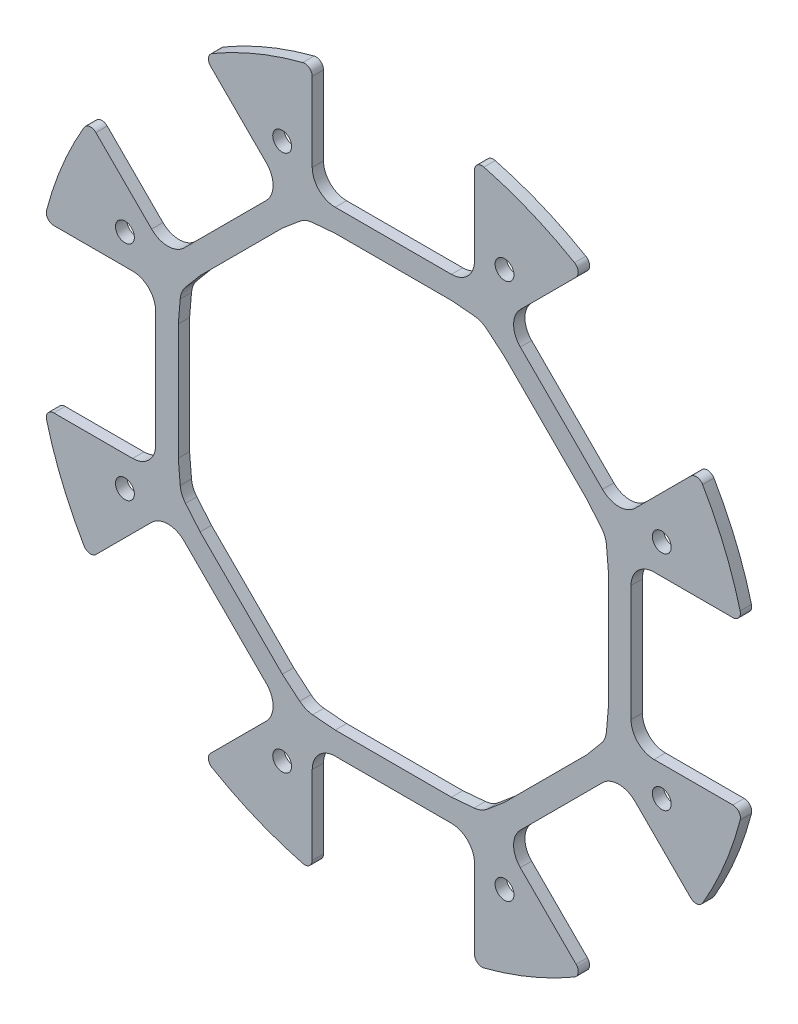
SolidWorks part; units mm, degrees
material "5052-H34"
ref_plane "正面" through (0, 0, 0) normal (0, 0, 1) x (1, 0, 0)
ref_plane "平面" through (0, 0, 0) normal (0, 1, 0) x (1, 0, 0)
ref_plane "右側面" through (0, 0, 0) normal (1, 0, 0) x (0, 0, -1)
sketch "ｽｹｯﾁ1" plane through (0, 0, 0) normal (0, 0, 1) x (1, 0, 0)
  circle A0 centre (0, 0) radius 47.5
  dimension "D1" = 95
extrude "ﾎﾞｽ - 押し出し1" add sketch "ｽｹｯﾁ1" along normal blind 1.5
sketch "ｽｹｯﾁ2" plane through (0, 0, 1.5) normal (0, 0, 1) x (1, 0, 0)
  line L0 (0, 0) -> (0, 47.5) construction
  line L1 (-10.75, 43.525) -> (-10.75, 52.5)
  line L2 (-10.75, 31.5) -> (10.75, 31.5)
  line L3 (-10.75, 31.5) -> (-10.75, 40.475)
  line L4 (-10.75, 52.5) -> (10.75, 52.5)
  line L5 (10.75, 31.5) -> (10.75, 40.475)
  line L6 (-10.75, 31.5) -> (10.75, 52.5) construction
  line L7 (-10.75, 52.5) -> (10.75, 31.5) construction
  line L8 (-13, 43.525) -> (-10.75, 43.525)
  line L9 (-13, 43.525) -> (-13, 40.475)
  line L10 (-13, 40.475) -> (-10.75, 40.475)
  line L11 (13, 43.525) -> (13, 40.475)
  line L12 (-13, 43.525) -> (13, 40.475) construction
  line L13 (-13, 40.475) -> (13, 43.525) construction
  line L14 (10.75, 43.525) -> (10.75, 52.5)
  line L15 (10.75, 43.525) -> (13, 43.525)
  line L17 (10.75, 40.475) -> (13, 40.475)
  circle A0 centre (0, 0) radius 47.5 construction
  point P5 (0, 42)
  point P10 (0, 42)
  dimension "D1" = 42
  dimension "D2" = 21.5
  dimension "D3" = 21
  dimension "D4" = 3.05
  dimension "D5" = 26
extrude "ｶｯﾄ - 押し出し1" cut sketch "ｽｹｯﾁ2" against normal through all
sketch "ｽｹｯﾁ3" plane through (0, 0, 1.5) normal (0, 0, 1) x (1, 0, 0)
  line L1 (-8.8388, -8.8388) -> (8.8388, -8.8388) construction
  line L2 (-8.8388, -8.8388) -> (-8.8388, 8.8388) construction
  line L3 (-8.8388, 8.8388) -> (8.8388, 8.8388) construction
  line L4 (8.8388, -8.8388) -> (8.8388, 8.8388) construction
  line L5 (-8.8388, -8.8388) -> (8.8388, 8.8388) construction
  line L6 (-8.8388, 8.8388) -> (8.8388, -8.8388) construction
  circle A0 centre (0, 0) radius 3.1
  circle A1 centre (0, 0) radius 6.5 construction
  circle A2 centre (0, 6.5) radius 1.6
  circle A3 centre (6.5, 0) radius 1.6
  circle A4 centre (0, -6.5) radius 1.6
  circle A5 centre (-6.5, 0) radius 1.6
  circle A6 centre (0, 0) radius 12.5 construction
  circle A7 centre (8.8388, 8.8388) radius 1.6
  circle A8 centre (8.8388, -8.8388) radius 1.6
  circle A9 centre (-8.8388, -8.8388) radius 1.6
  circle A10 centre (-8.8388, 8.8388) radius 1.6
  dimension "D1" = 6.2
  dimension "D2" = 13
  dimension "D3" = 3.2
  dimension "D5" = 25
  dimension "D6" = 3.2
  dimension "D4" = 4
  dimension "D7" = 4
extrude "ｶｯﾄ - 押し出し2" cut sketch "ｽｹｯﾁ3" against normal through all and the other way through all
sketch "ｽｹｯﾁ4" plane through (0, 0, 1.5) normal (0, 0, 1) x (1, 0, 0)
  line L0 (0, 31.5) -> (0, 0) construction
  line L1 (-10.75, 31.5) -> (10.75, 31.5) construction
  line L2 (0, 0) -> (14.7333, 35.5694) construction
  circle A0 centre (0, 0) radius 22.5 construction
  circle A1 centre (0, 0) radius 38.5 construction
  circle A2 centre (14.7333, 35.5694) radius 1.25
  circle A3 centre (8.6104, 20.7873) radius 1.25
  dimension "D1" = 45
  dimension "D2" = 77
  dimension "D4" = 2.5
  dimension "D3" = 22.5
extrude "ｶｯﾄ - 押し出し3" cut sketch "ｽｹｯﾁ4" against normal through all
sketch "ｽｹｯﾁ5" plane through (0, 0, 1.5) normal (0, 0, 1) x (1, 0, 0)
  line L0 (0, 0) -> (14.7333, 35.5694) construction
  line L1 (-10.75, 31.5) -> (10.75, 31.5) construction
  line L2 (-10.75, 31.5) -> (10.75, 31.5) construction
  line L3 (-7.1883, 26.5) -> (7.1883, 26.5)
  line L4 (-3.3281, 17.1806) -> (-7.1883, 26.5)
  line L5 (0, 31.5) -> (0, 0) construction
  line L6 (-10.75, 26.5) -> (10.75, 26.5) construction
  line L9 (-3.3281, 17.1806) -> (3.3281, 17.1806)
  line L10 (3.3281, 17.1806) -> (7.1883, 26.5)
  circle A0 centre (0, 0) radius 17.5 construction
  dimension "D3" = 35
  dimension "D2" = 7
  dimension "D1" = 5
extrude "ｶｯﾄ - 押し出し4" cut sketch "ｽｹｯﾁ5" against normal through all and the other way through all
fillet "ﾌｨﾚｯﾄ1" radius 1 6 edges at (-3.3281, 17.1806, 0.75) (3.3281, 17.1806, 0.75) (7.1883, 26.5, 0.75) (-7.1883, 26.5, 0.75) (10.75, 46.2676, 0.75) (-10.75, 46.2676, 0.75)
fillet "ﾌｨﾚｯﾄ2" radius 0.2 4 edges at (13, 43.525, 0.75) (13, 40.475, 0.75) (-13, 43.525, 0.75) (-13, 40.475, 0.75)
fillet "ﾌｨﾚｯﾄ3" radius 3.05 2 edges at (10.75, 31.5, 0.75) (-10.75, 31.5, 0.75)
ref_axis "軸1" through (0, 0, 0) along (0, 0, 1)
pattern_circular "円形ﾊﾟﾀｰﾝ1" count 8 over 360 about axis through (0, 0, 0) along (0, 0, 1) of "ｶｯﾄ - 押し出し1", "ﾌｨﾚｯﾄ1", "ｶｯﾄ - 押し出し4", "ｶｯﾄ - 押し出し3", "ﾌｨﾚｯﾄ2", "ﾌｨﾚｯﾄ3"
sketch "ｽｹｯﾁ6" plane through (0, 0, 1.5) normal (0, 0, 1) x (1, 0, 0)
  line L0 (7.7, 28.5) -> (-7.7, 28.5)
  line L1 (7.7, 28.5) -> (16.8291, 27.7186)
  line L2 (-7.7, 28.5) -> (-16.8291, 27.7186)
  line L3 (14.7078, 25.5973) -> (7.7, 31.5)
  line L4 (25.5973, 14.7078) -> (14.7078, 25.5973)
  line L5 (25.5973, 14.7078) -> (31.5, 7.7)
  line L6 (28.5, 7.7) -> (27.7186, 16.8291)
  line L7 (28.5, -7.7) -> (28.5, 7.7)
  line L8 (28.5, -7.7) -> (27.7186, -16.8291)
  line L9 (25.5973, -14.7078) -> (31.5, -7.7)
  line L10 (14.7078, -25.5973) -> (25.5973, -14.7078)
  line L11 (14.7078, -25.5973) -> (7.7, -31.5)
  line L12 (7.7, -28.5) -> (16.8291, -27.7186)
  line L13 (-7.7, -28.5) -> (7.7, -28.5)
  line L14 (-7.7, -28.5) -> (-16.8291, -27.7186)
  line L15 (-14.7078, -25.5973) -> (-7.7, -31.5)
  line L16 (-25.5973, -14.7078) -> (-14.7078, -25.5973)
  line L17 (-25.5973, -14.7078) -> (-31.5, -7.7)
  line L18 (-28.5, -7.7) -> (-27.7186, -16.8291)
  line L19 (-28.5, 7.7) -> (-28.5, -7.7)
  line L20 (-28.5, 7.7) -> (-27.7186, 16.8291)
  line L21 (-25.5973, 14.7078) -> (-31.5, 7.7)
  line L22 (-14.7078, 25.5973) -> (-25.5973, 14.7078)
  line L23 (-14.7078, 25.5973) -> (-7.7, 31.5)
  line L88 (39.4148, 24.212) -> (38.3782, 23.1754)
  line L89 (38.3782, 23.1754) -> (39.8278, 21.7259)
  line L90 (39.8278, 21.443) -> (37.954, 19.5692)
  line L91 (37.6711, 19.5692) -> (36.2215, 21.0187)
  line L92 (36.2215, 21.0187) -> (32.0319, 16.8291)
  line L93 (27.7186, 16.8291) -> (16.8291, 27.7186)
  line L94 (16.8291, 32.0319) -> (21.0187, 36.2215)
  line L95 (21.0187, 36.2215) -> (19.5692, 37.6711)
  line L96 (19.5692, 37.954) -> (21.443, 39.8278)
  line L97 (21.7259, 39.8278) -> (23.1754, 38.3782)
  line L98 (23.1754, 38.3782) -> (24.212, 39.4148)
  line L99 (10.75, 44.991) -> (10.75, 43.525)
  line L100 (10.75, 43.525) -> (12.8, 43.525)
  line L101 (13, 43.325) -> (13, 40.675)
  line L102 (12.8, 40.475) -> (10.75, 40.475)
  line L103 (10.75, 40.475) -> (10.75, 34.55)
  line L104 (7.7, 31.5) -> (-7.7, 31.5)
  line L105 (-10.75, 34.55) -> (-10.75, 40.475)
  line L106 (-10.75, 40.475) -> (-12.8, 40.475)
  line L107 (-13, 40.675) -> (-13, 43.325)
  line L108 (-12.8, 43.525) -> (-10.75, 43.525)
  line L109 (-10.75, 43.525) -> (-10.75, 44.991)
  line L110 (-24.212, 39.4148) -> (-23.1754, 38.3782)
  line L111 (-23.1754, 38.3782) -> (-21.7259, 39.8278)
  line L112 (-21.443, 39.8278) -> (-19.5692, 37.954)
  line L113 (-19.5692, 37.6711) -> (-21.0187, 36.2215)
  line L114 (-21.0187, 36.2215) -> (-16.8291, 32.0319)
  line L115 (-16.8291, 27.7186) -> (-27.7186, 16.8291)
  line L116 (-32.0319, 16.8291) -> (-36.2215, 21.0187)
  line L117 (-36.2215, 21.0187) -> (-37.6711, 19.5692)
  line L118 (-37.954, 19.5692) -> (-39.8278, 21.443)
  line L119 (-39.8278, 21.7259) -> (-38.3782, 23.1754)
  line L120 (-38.3782, 23.1754) -> (-39.4148, 24.212)
  line L121 (-44.991, 10.75) -> (-43.525, 10.75)
  line L122 (-43.525, 10.75) -> (-43.525, 12.8)
  line L123 (-43.325, 13) -> (-40.675, 13)
  line L124 (-40.475, 12.8) -> (-40.475, 10.75)
  line L125 (-40.475, 10.75) -> (-34.55, 10.75)
  line L126 (-31.5, 7.7) -> (-31.5, -7.7)
  line L127 (-34.55, -10.75) -> (-40.475, -10.75)
  line L128 (-40.475, -10.75) -> (-40.475, -12.8)
  line L129 (-40.675, -13) -> (-43.325, -13)
  line L130 (-43.525, -12.8) -> (-43.525, -10.75)
  line L131 (-43.525, -10.75) -> (-44.991, -10.75)
  line L132 (-39.4148, -24.212) -> (-38.3782, -23.1754)
  line L133 (-38.3782, -23.1754) -> (-39.8278, -21.7259)
  line L134 (-39.8278, -21.443) -> (-37.954, -19.5692)
  line L135 (-37.6711, -19.5692) -> (-36.2215, -21.0187)
  line L136 (-36.2215, -21.0187) -> (-32.0319, -16.8291)
  line L137 (-27.7186, -16.8291) -> (-16.8291, -27.7186)
  line L138 (-16.8291, -32.0319) -> (-21.0187, -36.2215)
  line L139 (-21.0187, -36.2215) -> (-19.5692, -37.6711)
  line L140 (-19.5692, -37.954) -> (-21.443, -39.8278)
  line L141 (-21.7259, -39.8278) -> (-23.1754, -38.3782)
  line L142 (-23.1754, -38.3782) -> (-24.212, -39.4148)
  line L143 (-10.75, -44.991) -> (-10.75, -43.525)
  line L144 (-10.75, -43.525) -> (-12.8, -43.525)
  line L145 (-13, -43.325) -> (-13, -40.675)
  line L146 (-12.8, -40.475) -> (-10.75, -40.475)
  line L147 (-10.75, -40.475) -> (-10.75, -34.55)
  line L148 (-7.7, -31.5) -> (7.7, -31.5)
  line L149 (10.75, -34.55) -> (10.75, -40.475)
  line L150 (10.75, -40.475) -> (12.8, -40.475)
  line L151 (13, -40.675) -> (13, -43.325)
  line L152 (12.8, -43.525) -> (10.75, -43.525)
  line L153 (10.75, -43.525) -> (10.75, -44.991)
  line L154 (24.212, -39.4148) -> (23.1754, -38.3782)
  line L155 (23.1754, -38.3782) -> (21.7259, -39.8278)
  line L156 (21.443, -39.8278) -> (19.5692, -37.954)
  line L157 (19.5692, -37.6711) -> (21.0187, -36.2215)
  line L158 (21.0187, -36.2215) -> (16.8291, -32.0319)
  line L159 (16.8291, -27.7186) -> (27.7186, -16.8291)
  line L160 (32.0319, -16.8291) -> (36.2215, -21.0187)
  line L161 (36.2215, -21.0187) -> (37.6711, -19.5692)
  line L162 (37.954, -19.5692) -> (39.8278, -21.443)
  line L163 (39.8278, -21.7259) -> (38.3782, -23.1754)
  line L164 (38.3782, -23.1754) -> (39.4148, -24.212)
  line L165 (44.991, -10.75) -> (43.525, -10.75)
  line L166 (43.525, -10.75) -> (43.525, -12.8)
  line L167 (43.325, -13) -> (40.675, -13)
  line L168 (40.475, -12.8) -> (40.475, -10.75)
  line L169 (40.475, -10.75) -> (34.55, -10.75)
  line L170 (31.5, -7.7) -> (31.5, 7.7)
  line L171 (34.55, 10.75) -> (40.475, 10.75)
  line L172 (40.475, 10.75) -> (40.475, 12.8)
  line L173 (40.675, 13) -> (43.325, 13)
  line L174 (43.525, 12.8) -> (43.525, 10.75)
  line L175 (43.525, 10.75) -> (44.991, 10.75)
  line L176 (39.4148, 24.212) -> (38.3782, 23.1754)
  line L177 (38.3782, 23.1754) -> (39.8278, 21.7259)
  line L178 (39.8278, 21.443) -> (37.954, 19.5692)
  line L179 (37.6711, 19.5692) -> (36.2215, 21.0187)
  line L180 (36.2215, 21.0187) -> (32.0319, 16.8291)
  line L181 (27.7186, 16.8291) -> (16.8291, 27.7186)
  line L182 (16.8291, 32.0319) -> (21.0187, 36.2215)
  line L183 (21.0187, 36.2215) -> (19.5692, 37.6711)
  line L184 (19.5692, 37.954) -> (21.443, 39.8278)
  line L185 (21.7259, 39.8278) -> (23.1754, 38.3782)
  line L186 (23.1754, 38.3782) -> (24.212, 39.4148)
  line L187 (10.75, 44.991) -> (10.75, 43.525)
  line L188 (10.75, 43.525) -> (12.8, 43.525)
  line L189 (13, 43.325) -> (13, 40.675)
  line L190 (12.8, 40.475) -> (10.75, 40.475)
  line L191 (10.75, 40.475) -> (10.75, 34.55)
  line L192 (7.7, 31.5) -> (-7.7, 31.5)
  line L193 (-10.75, 34.55) -> (-10.75, 40.475)
  line L194 (-10.75, 40.475) -> (-12.8, 40.475)
  line L195 (-13, 40.675) -> (-13, 43.325)
  line L196 (-12.8, 43.525) -> (-10.75, 43.525)
  line L197 (-10.75, 43.525) -> (-10.75, 44.991)
  line L198 (-24.212, 39.4148) -> (-23.1754, 38.3782)
  line L199 (-23.1754, 38.3782) -> (-21.7259, 39.8278)
  line L200 (-21.443, 39.8278) -> (-19.5692, 37.954)
  line L201 (-19.5692, 37.6711) -> (-21.0187, 36.2215)
  line L202 (-21.0187, 36.2215) -> (-16.8291, 32.0319)
  line L203 (-16.8291, 27.7186) -> (-27.7186, 16.8291)
  line L204 (-32.0319, 16.8291) -> (-36.2215, 21.0187)
  line L205 (-36.2215, 21.0187) -> (-37.6711, 19.5692)
  line L206 (-37.954, 19.5692) -> (-39.8278, 21.443)
  line L207 (-39.8278, 21.7259) -> (-38.3782, 23.1754)
  line L208 (-38.3782, 23.1754) -> (-39.4148, 24.212)
  line L209 (-44.991, 10.75) -> (-43.525, 10.75)
  line L210 (-43.525, 10.75) -> (-43.525, 12.8)
  line L211 (-43.325, 13) -> (-40.675, 13)
  line L212 (-40.475, 12.8) -> (-40.475, 10.75)
  line L213 (-40.475, 10.75) -> (-34.55, 10.75)
  line L214 (-31.5, 7.7) -> (-31.5, -7.7)
  line L215 (-34.55, -10.75) -> (-40.475, -10.75)
  line L216 (-40.475, -10.75) -> (-40.475, -12.8)
  line L217 (-40.675, -13) -> (-43.325, -13)
  line L218 (-43.525, -12.8) -> (-43.525, -10.75)
  line L219 (-43.525, -10.75) -> (-44.991, -10.75)
  line L220 (-39.4148, -24.212) -> (-38.3782, -23.1754)
  line L221 (-38.3782, -23.1754) -> (-39.8278, -21.7259)
  line L222 (-39.8278, -21.443) -> (-37.954, -19.5692)
  line L223 (-37.6711, -19.5692) -> (-36.2215, -21.0187)
  line L224 (-36.2215, -21.0187) -> (-32.0319, -16.8291)
  line L225 (-27.7186, -16.8291) -> (-16.8291, -27.7186)
  line L226 (-16.8291, -32.0319) -> (-21.0187, -36.2215)
  line L227 (-21.0187, -36.2215) -> (-19.5692, -37.6711)
  line L228 (-19.5692, -37.954) -> (-21.443, -39.8278)
  line L229 (-21.7259, -39.8278) -> (-23.1754, -38.3782)
  line L230 (-23.1754, -38.3782) -> (-24.212, -39.4148)
  line L231 (-10.75, -44.991) -> (-10.75, -43.525)
  line L232 (-10.75, -43.525) -> (-12.8, -43.525)
  line L233 (-13, -43.325) -> (-13, -40.675)
  line L234 (-12.8, -40.475) -> (-10.75, -40.475)
  line L235 (-10.75, -40.475) -> (-10.75, -34.55)
  line L236 (-7.7, -31.5) -> (7.7, -31.5)
  line L237 (10.75, -34.55) -> (10.75, -40.475)
  line L238 (10.75, -40.475) -> (12.8, -40.475)
  line L239 (13, -40.675) -> (13, -43.325)
  line L240 (12.8, -43.525) -> (10.75, -43.525)
  line L241 (10.75, -43.525) -> (10.75, -44.991)
  line L242 (24.212, -39.4148) -> (23.1754, -38.3782)
  line L243 (23.1754, -38.3782) -> (21.7259, -39.8278)
  line L244 (21.443, -39.8278) -> (19.5692, -37.954)
  line L245 (19.5692, -37.6711) -> (21.0187, -36.2215)
  line L246 (21.0187, -36.2215) -> (16.8291, -32.0319)
  line L247 (16.8291, -27.7186) -> (27.7186, -16.8291)
  line L248 (32.0319, -16.8291) -> (36.2215, -21.0187)
  line L249 (36.2215, -21.0187) -> (37.6711, -19.5692)
  line L250 (37.954, -19.5692) -> (39.8278, -21.443)
  line L251 (39.8278, -21.7259) -> (38.3782, -23.1754)
  line L252 (38.3782, -23.1754) -> (39.4148, -24.212)
  line L253 (44.991, -10.75) -> (43.525, -10.75)
  line L254 (43.525, -10.75) -> (43.525, -12.8)
  line L255 (43.325, -13) -> (40.675, -13)
  line L256 (40.475, -12.8) -> (40.475, -10.75)
  line L257 (40.475, -10.75) -> (34.55, -10.75)
  line L258 (31.5, -7.7) -> (31.5, 7.7)
  line L259 (34.55, 10.75) -> (40.475, 10.75)
  line L260 (40.475, 10.75) -> (40.475, 12.8)
  line L261 (40.675, 13) -> (43.325, 13)
  line L262 (43.525, 12.8) -> (43.525, 10.75)
  line L263 (43.525, 10.75) -> (44.991, 10.75)
  arc A72 (45.9585, 12.0027) -> (40.9848, 24.0104) centre (0, 0) ccw
  arc A73 (40.9848, 24.0104) -> (39.4148, 24.212) centre (40.1219, 23.5049) ccw
  arc A74 (39.8278, 21.443) -> (39.8278, 21.7259) centre (39.6864, 21.5844) ccw
  arc A75 (37.6711, 19.5692) -> (37.954, 19.5692) centre (37.8125, 19.7106) ccw
  arc A76 (27.7186, 16.8291) -> (32.0319, 16.8291) centre (29.8753, 18.9858) ccw
  arc A77 (16.8291, 32.0319) -> (16.8291, 27.7186) centre (18.9858, 29.8753) ccw
  arc A78 (19.5692, 37.954) -> (19.5692, 37.6711) centre (19.7106, 37.8125) ccw
  arc A79 (21.7259, 39.8278) -> (21.443, 39.8278) centre (21.5844, 39.6864) ccw
  arc A80 (24.212, 39.4148) -> (24.0104, 40.9848) centre (23.5049, 40.1219) ccw
  arc A81 (24.0104, 40.9848) -> (12.0027, 45.9585) centre (0, 0) ccw
  arc A82 (12.0027, 45.9585) -> (10.75, 44.991) centre (11.75, 44.991) ccw
  arc A83 (13, 43.325) -> (12.8, 43.525) centre (12.8, 43.325) ccw
  arc A84 (12.8, 40.475) -> (13, 40.675) centre (12.8, 40.675) ccw
  arc A85 (7.7, 31.5) -> (10.75, 34.55) centre (7.7, 34.55) ccw
  arc A86 (-10.75, 34.55) -> (-7.7, 31.5) centre (-7.7, 34.55) ccw
  arc A87 (-13, 40.675) -> (-12.8, 40.475) centre (-12.8, 40.675) ccw
  arc A88 (-12.8, 43.525) -> (-13, 43.325) centre (-12.8, 43.325) ccw
  arc A89 (-10.75, 44.991) -> (-12.0027, 45.9585) centre (-11.75, 44.991) ccw
  arc A90 (-12.0027, 45.9585) -> (-24.0104, 40.9848) centre (0, 0) ccw
  arc A91 (-24.0104, 40.9848) -> (-24.212, 39.4148) centre (-23.5049, 40.1219) ccw
  arc A92 (-21.443, 39.8278) -> (-21.7259, 39.8278) centre (-21.5844, 39.6864) ccw
  arc A93 (-19.5692, 37.6711) -> (-19.5692, 37.954) centre (-19.7106, 37.8125) ccw
  arc A94 (-16.8291, 27.7186) -> (-16.8291, 32.0319) centre (-18.9858, 29.8753) ccw
  arc A95 (-32.0319, 16.8291) -> (-27.7186, 16.8291) centre (-29.8753, 18.9858) ccw
  arc A96 (-37.954, 19.5692) -> (-37.6711, 19.5692) centre (-37.8125, 19.7106) ccw
  arc A97 (-39.8278, 21.7259) -> (-39.8278, 21.443) centre (-39.6864, 21.5844) ccw
  arc A98 (-39.4148, 24.212) -> (-40.9848, 24.0104) centre (-40.1219, 23.5049) ccw
  arc A99 (-40.9848, 24.0104) -> (-45.9585, 12.0027) centre (0, 0) ccw
  arc A100 (-45.9585, 12.0027) -> (-44.991, 10.75) centre (-44.991, 11.75) ccw
  arc A101 (-43.325, 13) -> (-43.525, 12.8) centre (-43.325, 12.8) ccw
  arc A102 (-40.475, 12.8) -> (-40.675, 13) centre (-40.675, 12.8) ccw
  arc A103 (-31.5, 7.7) -> (-34.55, 10.75) centre (-34.55, 7.7) ccw
  arc A104 (-34.55, -10.75) -> (-31.5, -7.7) centre (-34.55, -7.7) ccw
  arc A105 (-40.675, -13) -> (-40.475, -12.8) centre (-40.675, -12.8) ccw
  arc A106 (-43.525, -12.8) -> (-43.325, -13) centre (-43.325, -12.8) ccw
  arc A107 (-44.991, -10.75) -> (-45.9585, -12.0027) centre (-44.991, -11.75) ccw
  arc A108 (-45.9585, -12.0027) -> (-40.9848, -24.0104) centre (0, 0) ccw
  arc A109 (-40.9848, -24.0104) -> (-39.4148, -24.212) centre (-40.1219, -23.5049) ccw
  arc A110 (-39.8278, -21.443) -> (-39.8278, -21.7259) centre (-39.6864, -21.5844) ccw
  arc A111 (-37.6711, -19.5692) -> (-37.954, -19.5692) centre (-37.8125, -19.7106) ccw
  arc A112 (-27.7186, -16.8291) -> (-32.0319, -16.8291) centre (-29.8753, -18.9858) ccw
  arc A113 (-16.8291, -32.0319) -> (-16.8291, -27.7186) centre (-18.9858, -29.8753) ccw
  arc A114 (-19.5692, -37.954) -> (-19.5692, -37.6711) centre (-19.7106, -37.8125) ccw
  arc A115 (-21.7259, -39.8278) -> (-21.443, -39.8278) centre (-21.5844, -39.6864) ccw
  arc A116 (-24.212, -39.4148) -> (-24.0104, -40.9848) centre (-23.5049, -40.1219) ccw
  arc A117 (-24.0104, -40.9848) -> (-12.0027, -45.9585) centre (0, 0) ccw
  arc A118 (-12.0027, -45.9585) -> (-10.75, -44.991) centre (-11.75, -44.991) ccw
  arc A119 (-13, -43.325) -> (-12.8, -43.525) centre (-12.8, -43.325) ccw
  arc A120 (-12.8, -40.475) -> (-13, -40.675) centre (-12.8, -40.675) ccw
  arc A121 (-7.7, -31.5) -> (-10.75, -34.55) centre (-7.7, -34.55) ccw
  arc A122 (10.75, -34.55) -> (7.7, -31.5) centre (7.7, -34.55) ccw
  arc A123 (13, -40.675) -> (12.8, -40.475) centre (12.8, -40.675) ccw
  arc A124 (12.8, -43.525) -> (13, -43.325) centre (12.8, -43.325) ccw
  arc A125 (10.75, -44.991) -> (12.0027, -45.9585) centre (11.75, -44.991) ccw
  arc A126 (12.0027, -45.9585) -> (24.0104, -40.9848) centre (0, 0) ccw
  arc A127 (24.0104, -40.9848) -> (24.212, -39.4148) centre (23.5049, -40.1219) ccw
  arc A128 (21.443, -39.8278) -> (21.7259, -39.8278) centre (21.5844, -39.6864) ccw
  arc A129 (19.5692, -37.6711) -> (19.5692, -37.954) centre (19.7106, -37.8125) ccw
  arc A130 (16.8291, -27.7186) -> (16.8291, -32.0319) centre (18.9858, -29.8753) ccw
  arc A131 (32.0319, -16.8291) -> (27.7186, -16.8291) centre (29.8753, -18.9858) ccw
  arc A132 (37.954, -19.5692) -> (37.6711, -19.5692) centre (37.8125, -19.7106) ccw
  arc A133 (39.8278, -21.7259) -> (39.8278, -21.443) centre (39.6864, -21.5844) ccw
  arc A134 (39.4148, -24.212) -> (40.9848, -24.0104) centre (40.1219, -23.5049) ccw
  arc A135 (40.9848, -24.0104) -> (45.9585, -12.0027) centre (0, 0) ccw
  arc A136 (45.9585, -12.0027) -> (44.991, -10.75) centre (44.991, -11.75) ccw
  arc A137 (43.325, -13) -> (43.525, -12.8) centre (43.325, -12.8) ccw
  arc A138 (40.475, -12.8) -> (40.675, -13) centre (40.675, -12.8) ccw
  arc A139 (31.5, -7.7) -> (34.55, -10.75) centre (34.55, -7.7) ccw
  arc A140 (34.55, 10.75) -> (31.5, 7.7) centre (34.55, 7.7) ccw
  arc A141 (40.675, 13) -> (40.475, 12.8) centre (40.675, 12.8) ccw
  arc A142 (43.525, 12.8) -> (43.325, 13) centre (43.325, 12.8) ccw
  arc A143 (44.991, 10.75) -> (45.9585, 12.0027) centre (44.991, 11.75) ccw
  arc A144 (45.9585, 12.0027) -> (40.9848, 24.0104) centre (0, 0) ccw
  arc A145 (40.9848, 24.0104) -> (39.4148, 24.212) centre (40.1219, 23.5049) ccw
  arc A146 (39.8278, 21.443) -> (39.8278, 21.7259) centre (39.6864, 21.5844) ccw
  arc A147 (37.6711, 19.5692) -> (37.954, 19.5692) centre (37.8125, 19.7106) ccw
  arc A148 (27.7186, 16.8291) -> (32.0319, 16.8291) centre (29.8753, 18.9858) ccw
  arc A149 (16.8291, 32.0319) -> (16.8291, 27.7186) centre (18.9858, 29.8753) ccw
  arc A150 (19.5692, 37.954) -> (19.5692, 37.6711) centre (19.7106, 37.8125) ccw
  arc A151 (21.7259, 39.8278) -> (21.443, 39.8278) centre (21.5844, 39.6864) ccw
  arc A152 (24.212, 39.4148) -> (24.0104, 40.9848) centre (23.5049, 40.1219) ccw
  arc A153 (24.0104, 40.9848) -> (12.0027, 45.9585) centre (0, 0) ccw
  arc A154 (12.0027, 45.9585) -> (10.75, 44.991) centre (11.75, 44.991) ccw
  arc A155 (13, 43.325) -> (12.8, 43.525) centre (12.8, 43.325) ccw
  arc A156 (12.8, 40.475) -> (13, 40.675) centre (12.8, 40.675) ccw
  arc A157 (7.7, 31.5) -> (10.75, 34.55) centre (7.7, 34.55) ccw
  arc A158 (-10.75, 34.55) -> (-7.7, 31.5) centre (-7.7, 34.55) ccw
  arc A159 (-13, 40.675) -> (-12.8, 40.475) centre (-12.8, 40.675) ccw
  arc A160 (-12.8, 43.525) -> (-13, 43.325) centre (-12.8, 43.325) ccw
  arc A161 (-10.75, 44.991) -> (-12.0027, 45.9585) centre (-11.75, 44.991) ccw
  arc A162 (-12.0027, 45.9585) -> (-24.0104, 40.9848) centre (0, 0) ccw
  arc A163 (-24.0104, 40.9848) -> (-24.212, 39.4148) centre (-23.5049, 40.1219) ccw
  arc A164 (-21.443, 39.8278) -> (-21.7259, 39.8278) centre (-21.5844, 39.6864) ccw
  arc A165 (-19.5692, 37.6711) -> (-19.5692, 37.954) centre (-19.7106, 37.8125) ccw
  arc A166 (-16.8291, 27.7186) -> (-16.8291, 32.0319) centre (-18.9858, 29.8753) ccw
  arc A167 (-32.0319, 16.8291) -> (-27.7186, 16.8291) centre (-29.8753, 18.9858) ccw
  arc A168 (-37.954, 19.5692) -> (-37.6711, 19.5692) centre (-37.8125, 19.7106) ccw
  arc A169 (-39.8278, 21.7259) -> (-39.8278, 21.443) centre (-39.6864, 21.5844) ccw
  arc A170 (-39.4148, 24.212) -> (-40.9848, 24.0104) centre (-40.1219, 23.5049) ccw
  arc A171 (-40.9848, 24.0104) -> (-45.9585, 12.0027) centre (0, 0) ccw
  arc A172 (-45.9585, 12.0027) -> (-44.991, 10.75) centre (-44.991, 11.75) ccw
  arc A173 (-43.325, 13) -> (-43.525, 12.8) centre (-43.325, 12.8) ccw
  arc A174 (-40.475, 12.8) -> (-40.675, 13) centre (-40.675, 12.8) ccw
  arc A175 (-31.5, 7.7) -> (-34.55, 10.75) centre (-34.55, 7.7) ccw
  arc A176 (-34.55, -10.75) -> (-31.5, -7.7) centre (-34.55, -7.7) ccw
  arc A177 (-40.675, -13) -> (-40.475, -12.8) centre (-40.675, -12.8) ccw
  arc A178 (-43.525, -12.8) -> (-43.325, -13) centre (-43.325, -12.8) ccw
  arc A179 (-44.991, -10.75) -> (-45.9585, -12.0027) centre (-44.991, -11.75) ccw
  arc A180 (-45.9585, -12.0027) -> (-40.9848, -24.0104) centre (0, 0) ccw
  arc A181 (-40.9848, -24.0104) -> (-39.4148, -24.212) centre (-40.1219, -23.5049) ccw
  arc A182 (-39.8278, -21.443) -> (-39.8278, -21.7259) centre (-39.6864, -21.5844) ccw
  arc A183 (-37.6711, -19.5692) -> (-37.954, -19.5692) centre (-37.8125, -19.7106) ccw
  arc A184 (-27.7186, -16.8291) -> (-32.0319, -16.8291) centre (-29.8753, -18.9858) ccw
  arc A185 (-16.8291, -32.0319) -> (-16.8291, -27.7186) centre (-18.9858, -29.8753) ccw
  arc A186 (-19.5692, -37.954) -> (-19.5692, -37.6711) centre (-19.7106, -37.8125) ccw
  arc A187 (-21.7259, -39.8278) -> (-21.443, -39.8278) centre (-21.5844, -39.6864) ccw
  arc A188 (-24.212, -39.4148) -> (-24.0104, -40.9848) centre (-23.5049, -40.1219) ccw
  arc A189 (-24.0104, -40.9848) -> (-12.0027, -45.9585) centre (0, 0) ccw
  arc A190 (-12.0027, -45.9585) -> (-10.75, -44.991) centre (-11.75, -44.991) ccw
  arc A191 (-13, -43.325) -> (-12.8, -43.525) centre (-12.8, -43.325) ccw
  arc A192 (-12.8, -40.475) -> (-13, -40.675) centre (-12.8, -40.675) ccw
  arc A193 (-7.7, -31.5) -> (-10.75, -34.55) centre (-7.7, -34.55) ccw
  arc A194 (10.75, -34.55) -> (7.7, -31.5) centre (7.7, -34.55) ccw
  arc A195 (13, -40.675) -> (12.8, -40.475) centre (12.8, -40.675) ccw
  arc A196 (12.8, -43.525) -> (13, -43.325) centre (12.8, -43.325) ccw
  arc A197 (10.75, -44.991) -> (12.0027, -45.9585) centre (11.75, -44.991) ccw
  arc A198 (12.0027, -45.9585) -> (24.0104, -40.9848) centre (0, 0) ccw
  arc A199 (24.0104, -40.9848) -> (24.212, -39.4148) centre (23.5049, -40.1219) ccw
  arc A200 (21.443, -39.8278) -> (21.7259, -39.8278) centre (21.5844, -39.6864) ccw
  arc A201 (19.5692, -37.6711) -> (19.5692, -37.954) centre (19.7106, -37.8125) ccw
  arc A202 (16.8291, -27.7186) -> (16.8291, -32.0319) centre (18.9858, -29.8753) ccw
  arc A203 (32.0319, -16.8291) -> (27.7186, -16.8291) centre (29.8753, -18.9858) ccw
  arc A204 (37.954, -19.5692) -> (37.6711, -19.5692) centre (37.8125, -19.7106) ccw
  arc A205 (39.8278, -21.7259) -> (39.8278, -21.443) centre (39.6864, -21.5844) ccw
  arc A206 (39.4148, -24.212) -> (40.9848, -24.0104) centre (40.1219, -23.5049) ccw
  arc A207 (40.9848, -24.0104) -> (45.9585, -12.0027) centre (0, 0) ccw
  arc A208 (45.9585, -12.0027) -> (44.991, -10.75) centre (44.991, -11.75) ccw
  arc A209 (43.325, -13) -> (43.525, -12.8) centre (43.325, -12.8) ccw
  arc A210 (40.475, -12.8) -> (40.675, -13) centre (40.675, -12.8) ccw
  arc A211 (31.5, -7.7) -> (34.55, -10.75) centre (34.55, -7.7) ccw
  arc A212 (34.55, 10.75) -> (31.5, 7.7) centre (34.55, 7.7) ccw
  arc A213 (40.675, 13) -> (40.475, 12.8) centre (40.675, 12.8) ccw
  arc A214 (43.525, 12.8) -> (43.325, 13) centre (43.325, 12.8) ccw
  arc A215 (44.991, 10.75) -> (45.9585, 12.0027) centre (44.991, 11.75) ccw
  dimension "D4" = 3
  dimension "D5" = 3
  dimension "D1" = 0
  dimension "D2" = 3
  dimension "D3" = 8
extrude "ｶｯﾄ - 押し出し5" cut sketch "ｽｹｯﾁ6" against normal through all contours L23 L22 L21 L20 L19 L18 L17 L16 L15 L14 L13 L12 L11 L10 L9 L8 L7 L6 L5 L4 L3 L1 L0 L2
sketch "ｽｹｯﾁ7" plane through (0, 0, 1.5) normal (0, 0, 1) x (1, 0, 0)
  line L0 (-10.75, 43.525) -> (-10.75, 40.475)
  line L1 (10.75, 43.525) -> (10.75, 40.475)
  line L2 (23.1754, 38.3782) -> (21.0187, 36.2215)
  line L3 (38.3782, 23.1754) -> (36.2215, 21.0187)
  line L4 (43.525, 10.75) -> (40.475, 10.75)
  line L5 (43.525, -10.75) -> (40.475, -10.75)
  line L6 (38.3782, -23.1754) -> (36.2215, -21.0187)
  line L7 (23.1754, -38.3782) -> (21.0187, -36.2215)
  line L8 (10.75, -43.525) -> (10.75, -40.475)
  line L9 (-10.75, -43.525) -> (-10.75, -40.475)
  line L10 (-23.1754, -38.3782) -> (-21.0187, -36.2215)
  line L11 (-38.3782, -23.1754) -> (-36.2215, -21.0187)
  line L12 (-43.525, -10.75) -> (-40.475, -10.75)
  line L13 (-43.525, 10.75) -> (-40.475, 10.75)
  line L14 (-38.3782, 23.1754) -> (-36.2215, 21.0187)
  line L15 (-23.1754, 38.3782) -> (-21.0187, 36.2215)
  line L88 (39.4148, 24.212) -> (38.3782, 23.1754)
  line L89 (38.3782, 23.1754) -> (39.8278, 21.7259)
  line L90 (39.8278, 21.443) -> (37.954, 19.5692)
  line L91 (37.6711, 19.5692) -> (36.2215, 21.0187)
  line L92 (36.2215, 21.0187) -> (32.0319, 16.8291)
  line L93 (27.7186, 16.8291) -> (16.8291, 27.7186)
  line L94 (16.8291, 32.0319) -> (21.0187, 36.2215)
  line L95 (21.0187, 36.2215) -> (19.5692, 37.6711)
  line L96 (19.5692, 37.954) -> (21.443, 39.8278)
  line L97 (21.7259, 39.8278) -> (23.1754, 38.3782)
  line L98 (23.1754, 38.3782) -> (24.212, 39.4148)
  line L99 (10.75, 44.991) -> (10.75, 43.525)
  line L100 (10.75, 43.525) -> (12.8, 43.525)
  line L101 (13, 43.325) -> (13, 40.675)
  line L102 (12.8, 40.475) -> (10.75, 40.475)
  line L103 (10.75, 40.475) -> (10.75, 34.55)
  line L104 (7.7, 31.5) -> (-7.7, 31.5)
  line L105 (-10.75, 34.55) -> (-10.75, 40.475)
  line L106 (-10.75, 40.475) -> (-12.8, 40.475)
  line L107 (-13, 40.675) -> (-13, 43.325)
  line L108 (-12.8, 43.525) -> (-10.75, 43.525)
  line L109 (-10.75, 43.525) -> (-10.75, 44.991)
  line L110 (-24.212, 39.4148) -> (-23.1754, 38.3782)
  line L111 (-23.1754, 38.3782) -> (-21.7259, 39.8278)
  line L112 (-21.443, 39.8278) -> (-19.5692, 37.954)
  line L113 (-19.5692, 37.6711) -> (-21.0187, 36.2215)
  line L114 (-21.0187, 36.2215) -> (-16.8291, 32.0319)
  line L115 (-16.8291, 27.7186) -> (-27.7186, 16.8291)
  line L116 (-32.0319, 16.8291) -> (-36.2215, 21.0187)
  line L117 (-36.2215, 21.0187) -> (-37.6711, 19.5692)
  line L118 (-37.954, 19.5692) -> (-39.8278, 21.443)
  line L119 (-39.8278, 21.7259) -> (-38.3782, 23.1754)
  line L120 (-38.3782, 23.1754) -> (-39.4148, 24.212)
  line L121 (-44.991, 10.75) -> (-43.525, 10.75)
  line L122 (-43.525, 10.75) -> (-43.525, 12.8)
  line L123 (-43.325, 13) -> (-40.675, 13)
  line L124 (-40.475, 12.8) -> (-40.475, 10.75)
  line L125 (-40.475, 10.75) -> (-34.55, 10.75)
  line L126 (-31.5, 7.7) -> (-31.5, -7.7)
  line L127 (-34.55, -10.75) -> (-40.475, -10.75)
  line L128 (-40.475, -10.75) -> (-40.475, -12.8)
  line L129 (-40.675, -13) -> (-43.325, -13)
  line L130 (-43.525, -12.8) -> (-43.525, -10.75)
  line L131 (-43.525, -10.75) -> (-44.991, -10.75)
  line L132 (-39.4148, -24.212) -> (-38.3782, -23.1754)
  line L133 (-38.3782, -23.1754) -> (-39.8278, -21.7259)
  line L134 (-39.8278, -21.443) -> (-37.954, -19.5692)
  line L135 (-37.6711, -19.5692) -> (-36.2215, -21.0187)
  line L136 (-36.2215, -21.0187) -> (-32.0319, -16.8291)
  line L137 (-27.7186, -16.8291) -> (-16.8291, -27.7186)
  line L138 (-16.8291, -32.0319) -> (-21.0187, -36.2215)
  line L139 (-21.0187, -36.2215) -> (-19.5692, -37.6711)
  line L140 (-19.5692, -37.954) -> (-21.443, -39.8278)
  line L141 (-21.7259, -39.8278) -> (-23.1754, -38.3782)
  line L142 (-23.1754, -38.3782) -> (-24.212, -39.4148)
  line L143 (-10.75, -44.991) -> (-10.75, -43.525)
  line L144 (-10.75, -43.525) -> (-12.8, -43.525)
  line L145 (-13, -43.325) -> (-13, -40.675)
  line L146 (-12.8, -40.475) -> (-10.75, -40.475)
  line L147 (-10.75, -40.475) -> (-10.75, -34.55)
  line L148 (-7.7, -31.5) -> (7.7, -31.5)
  line L149 (10.75, -34.55) -> (10.75, -40.475)
  line L150 (10.75, -40.475) -> (12.8, -40.475)
  line L151 (13, -40.675) -> (13, -43.325)
  line L152 (12.8, -43.525) -> (10.75, -43.525)
  line L153 (10.75, -43.525) -> (10.75, -44.991)
  line L154 (24.212, -39.4148) -> (23.1754, -38.3782)
  line L155 (23.1754, -38.3782) -> (21.7259, -39.8278)
  line L156 (21.443, -39.8278) -> (19.5692, -37.954)
  line L157 (19.5692, -37.6711) -> (21.0187, -36.2215)
  line L158 (21.0187, -36.2215) -> (16.8291, -32.0319)
  line L159 (16.8291, -27.7186) -> (27.7186, -16.8291)
  line L160 (32.0319, -16.8291) -> (36.2215, -21.0187)
  line L161 (36.2215, -21.0187) -> (37.6711, -19.5692)
  line L162 (37.954, -19.5692) -> (39.8278, -21.443)
  line L163 (39.8278, -21.7259) -> (38.3782, -23.1754)
  line L164 (38.3782, -23.1754) -> (39.4148, -24.212)
  line L165 (44.991, -10.75) -> (43.525, -10.75)
  line L166 (43.525, -10.75) -> (43.525, -12.8)
  line L167 (43.325, -13) -> (40.675, -13)
  line L168 (40.475, -12.8) -> (40.475, -10.75)
  line L169 (40.475, -10.75) -> (34.55, -10.75)
  line L170 (31.5, -7.7) -> (31.5, 7.7)
  line L171 (34.55, 10.75) -> (40.475, 10.75)
  line L172 (40.475, 10.75) -> (40.475, 12.8)
  line L173 (40.675, 13) -> (43.325, 13)
  line L174 (43.525, 12.8) -> (43.525, 10.75)
  line L175 (43.525, 10.75) -> (44.991, 10.75)
  line L176 (39.4148, 24.212) -> (38.3782, 23.1754)
  line L177 (38.3782, 23.1754) -> (39.8278, 21.7259)
  line L178 (39.8278, 21.443) -> (37.954, 19.5692)
  line L179 (37.6711, 19.5692) -> (36.2215, 21.0187)
  line L180 (36.2215, 21.0187) -> (32.0319, 16.8291)
  line L181 (27.7186, 16.8291) -> (16.8291, 27.7186)
  line L182 (16.8291, 32.0319) -> (21.0187, 36.2215)
  line L183 (21.0187, 36.2215) -> (19.5692, 37.6711)
  line L184 (19.5692, 37.954) -> (21.443, 39.8278)
  line L185 (21.7259, 39.8278) -> (23.1754, 38.3782)
  line L186 (23.1754, 38.3782) -> (24.212, 39.4148)
  line L187 (10.75, 44.991) -> (10.75, 43.525)
  line L188 (10.75, 43.525) -> (12.8, 43.525)
  line L189 (13, 43.325) -> (13, 40.675)
  line L190 (12.8, 40.475) -> (10.75, 40.475)
  line L191 (10.75, 40.475) -> (10.75, 34.55)
  line L192 (7.7, 31.5) -> (-7.7, 31.5)
  line L193 (-10.75, 34.55) -> (-10.75, 40.475)
  line L194 (-10.75, 40.475) -> (-12.8, 40.475)
  line L195 (-13, 40.675) -> (-13, 43.325)
  line L196 (-12.8, 43.525) -> (-10.75, 43.525)
  line L197 (-10.75, 43.525) -> (-10.75, 44.991)
  line L198 (-24.212, 39.4148) -> (-23.1754, 38.3782)
  line L199 (-23.1754, 38.3782) -> (-21.7259, 39.8278)
  line L200 (-21.443, 39.8278) -> (-19.5692, 37.954)
  line L201 (-19.5692, 37.6711) -> (-21.0187, 36.2215)
  line L202 (-21.0187, 36.2215) -> (-16.8291, 32.0319)
  line L203 (-16.8291, 27.7186) -> (-27.7186, 16.8291)
  line L204 (-32.0319, 16.8291) -> (-36.2215, 21.0187)
  line L205 (-36.2215, 21.0187) -> (-37.6711, 19.5692)
  line L206 (-37.954, 19.5692) -> (-39.8278, 21.443)
  line L207 (-39.8278, 21.7259) -> (-38.3782, 23.1754)
  line L208 (-38.3782, 23.1754) -> (-39.4148, 24.212)
  line L209 (-44.991, 10.75) -> (-43.525, 10.75)
  line L210 (-43.525, 10.75) -> (-43.525, 12.8)
  line L211 (-43.325, 13) -> (-40.675, 13)
  line L212 (-40.475, 12.8) -> (-40.475, 10.75)
  line L213 (-40.475, 10.75) -> (-34.55, 10.75)
  line L214 (-31.5, 7.7) -> (-31.5, -7.7)
  line L215 (-34.55, -10.75) -> (-40.475, -10.75)
  line L216 (-40.475, -10.75) -> (-40.475, -12.8)
  line L217 (-40.675, -13) -> (-43.325, -13)
  line L218 (-43.525, -12.8) -> (-43.525, -10.75)
  line L219 (-43.525, -10.75) -> (-44.991, -10.75)
  line L220 (-39.4148, -24.212) -> (-38.3782, -23.1754)
  line L221 (-38.3782, -23.1754) -> (-39.8278, -21.7259)
  line L222 (-39.8278, -21.443) -> (-37.954, -19.5692)
  line L223 (-37.6711, -19.5692) -> (-36.2215, -21.0187)
  line L224 (-36.2215, -21.0187) -> (-32.0319, -16.8291)
  line L225 (-27.7186, -16.8291) -> (-16.8291, -27.7186)
  line L226 (-16.8291, -32.0319) -> (-21.0187, -36.2215)
  line L227 (-21.0187, -36.2215) -> (-19.5692, -37.6711)
  line L228 (-19.5692, -37.954) -> (-21.443, -39.8278)
  line L229 (-21.7259, -39.8278) -> (-23.1754, -38.3782)
  line L230 (-23.1754, -38.3782) -> (-24.212, -39.4148)
  line L231 (-10.75, -44.991) -> (-10.75, -43.525)
  line L232 (-10.75, -43.525) -> (-12.8, -43.525)
  line L233 (-13, -43.325) -> (-13, -40.675)
  line L234 (-12.8, -40.475) -> (-10.75, -40.475)
  line L235 (-10.75, -40.475) -> (-10.75, -34.55)
  line L236 (-7.7, -31.5) -> (7.7, -31.5)
  line L237 (10.75, -34.55) -> (10.75, -40.475)
  line L238 (10.75, -40.475) -> (12.8, -40.475)
  line L239 (13, -40.675) -> (13, -43.325)
  line L240 (12.8, -43.525) -> (10.75, -43.525)
  line L241 (10.75, -43.525) -> (10.75, -44.991)
  line L242 (24.212, -39.4148) -> (23.1754, -38.3782)
  line L243 (23.1754, -38.3782) -> (21.7259, -39.8278)
  line L244 (21.443, -39.8278) -> (19.5692, -37.954)
  line L245 (19.5692, -37.6711) -> (21.0187, -36.2215)
  line L246 (21.0187, -36.2215) -> (16.8291, -32.0319)
  line L247 (16.8291, -27.7186) -> (27.7186, -16.8291)
  line L248 (32.0319, -16.8291) -> (36.2215, -21.0187)
  line L249 (36.2215, -21.0187) -> (37.6711, -19.5692)
  line L250 (37.954, -19.5692) -> (39.8278, -21.443)
  line L251 (39.8278, -21.7259) -> (38.3782, -23.1754)
  line L252 (38.3782, -23.1754) -> (39.4148, -24.212)
  line L253 (44.991, -10.75) -> (43.525, -10.75)
  line L254 (43.525, -10.75) -> (43.525, -12.8)
  line L255 (43.325, -13) -> (40.675, -13)
  line L256 (40.475, -12.8) -> (40.475, -10.75)
  line L257 (40.475, -10.75) -> (34.55, -10.75)
  line L258 (31.5, -7.7) -> (31.5, 7.7)
  line L259 (34.55, 10.75) -> (40.475, 10.75)
  line L260 (40.475, 10.75) -> (40.475, 12.8)
  line L261 (40.675, 13) -> (43.325, 13)
  line L262 (43.525, 12.8) -> (43.525, 10.75)
  line L263 (43.525, 10.75) -> (44.991, 10.75)
  arc A72 (45.9585, 12.0027) -> (40.9848, 24.0104) centre (0, 0) ccw
  arc A73 (40.9848, 24.0104) -> (39.4148, 24.212) centre (40.1219, 23.5049) ccw
  arc A74 (39.8278, 21.443) -> (39.8278, 21.7259) centre (39.6864, 21.5844) ccw
  arc A75 (37.6711, 19.5692) -> (37.954, 19.5692) centre (37.8125, 19.7106) ccw
  arc A76 (27.7186, 16.8291) -> (32.0319, 16.8291) centre (29.8753, 18.9858) ccw
  arc A77 (16.8291, 32.0319) -> (16.8291, 27.7186) centre (18.9858, 29.8753) ccw
  arc A78 (19.5692, 37.954) -> (19.5692, 37.6711) centre (19.7106, 37.8125) ccw
  arc A79 (21.7259, 39.8278) -> (21.443, 39.8278) centre (21.5844, 39.6864) ccw
  arc A80 (24.212, 39.4148) -> (24.0104, 40.9848) centre (23.5049, 40.1219) ccw
  arc A81 (24.0104, 40.9848) -> (12.0027, 45.9585) centre (0, 0) ccw
  arc A82 (12.0027, 45.9585) -> (10.75, 44.991) centre (11.75, 44.991) ccw
  arc A83 (13, 43.325) -> (12.8, 43.525) centre (12.8, 43.325) ccw
  arc A84 (12.8, 40.475) -> (13, 40.675) centre (12.8, 40.675) ccw
  arc A85 (7.7, 31.5) -> (10.75, 34.55) centre (7.7, 34.55) ccw
  arc A86 (-10.75, 34.55) -> (-7.7, 31.5) centre (-7.7, 34.55) ccw
  arc A87 (-13, 40.675) -> (-12.8, 40.475) centre (-12.8, 40.675) ccw
  arc A88 (-12.8, 43.525) -> (-13, 43.325) centre (-12.8, 43.325) ccw
  arc A89 (-10.75, 44.991) -> (-12.0027, 45.9585) centre (-11.75, 44.991) ccw
  arc A90 (-12.0027, 45.9585) -> (-24.0104, 40.9848) centre (0, 0) ccw
  arc A91 (-24.0104, 40.9848) -> (-24.212, 39.4148) centre (-23.5049, 40.1219) ccw
  arc A92 (-21.443, 39.8278) -> (-21.7259, 39.8278) centre (-21.5844, 39.6864) ccw
  arc A93 (-19.5692, 37.6711) -> (-19.5692, 37.954) centre (-19.7106, 37.8125) ccw
  arc A94 (-16.8291, 27.7186) -> (-16.8291, 32.0319) centre (-18.9858, 29.8753) ccw
  arc A95 (-32.0319, 16.8291) -> (-27.7186, 16.8291) centre (-29.8753, 18.9858) ccw
  arc A96 (-37.954, 19.5692) -> (-37.6711, 19.5692) centre (-37.8125, 19.7106) ccw
  arc A97 (-39.8278, 21.7259) -> (-39.8278, 21.443) centre (-39.6864, 21.5844) ccw
  arc A98 (-39.4148, 24.212) -> (-40.9848, 24.0104) centre (-40.1219, 23.5049) ccw
  arc A99 (-40.9848, 24.0104) -> (-45.9585, 12.0027) centre (0, 0) ccw
  arc A100 (-45.9585, 12.0027) -> (-44.991, 10.75) centre (-44.991, 11.75) ccw
  arc A101 (-43.325, 13) -> (-43.525, 12.8) centre (-43.325, 12.8) ccw
  arc A102 (-40.475, 12.8) -> (-40.675, 13) centre (-40.675, 12.8) ccw
  arc A103 (-31.5, 7.7) -> (-34.55, 10.75) centre (-34.55, 7.7) ccw
  arc A104 (-34.55, -10.75) -> (-31.5, -7.7) centre (-34.55, -7.7) ccw
  arc A105 (-40.675, -13) -> (-40.475, -12.8) centre (-40.675, -12.8) ccw
  arc A106 (-43.525, -12.8) -> (-43.325, -13) centre (-43.325, -12.8) ccw
  arc A107 (-44.991, -10.75) -> (-45.9585, -12.0027) centre (-44.991, -11.75) ccw
  arc A108 (-45.9585, -12.0027) -> (-40.9848, -24.0104) centre (0, 0) ccw
  arc A109 (-40.9848, -24.0104) -> (-39.4148, -24.212) centre (-40.1219, -23.5049) ccw
  arc A110 (-39.8278, -21.443) -> (-39.8278, -21.7259) centre (-39.6864, -21.5844) ccw
  arc A111 (-37.6711, -19.5692) -> (-37.954, -19.5692) centre (-37.8125, -19.7106) ccw
  arc A112 (-27.7186, -16.8291) -> (-32.0319, -16.8291) centre (-29.8753, -18.9858) ccw
  arc A113 (-16.8291, -32.0319) -> (-16.8291, -27.7186) centre (-18.9858, -29.8753) ccw
  arc A114 (-19.5692, -37.954) -> (-19.5692, -37.6711) centre (-19.7106, -37.8125) ccw
  arc A115 (-21.7259, -39.8278) -> (-21.443, -39.8278) centre (-21.5844, -39.6864) ccw
  arc A116 (-24.212, -39.4148) -> (-24.0104, -40.9848) centre (-23.5049, -40.1219) ccw
  arc A117 (-24.0104, -40.9848) -> (-12.0027, -45.9585) centre (0, 0) ccw
  arc A118 (-12.0027, -45.9585) -> (-10.75, -44.991) centre (-11.75, -44.991) ccw
  arc A119 (-13, -43.325) -> (-12.8, -43.525) centre (-12.8, -43.325) ccw
  arc A120 (-12.8, -40.475) -> (-13, -40.675) centre (-12.8, -40.675) ccw
  arc A121 (-7.7, -31.5) -> (-10.75, -34.55) centre (-7.7, -34.55) ccw
  arc A122 (10.75, -34.55) -> (7.7, -31.5) centre (7.7, -34.55) ccw
  arc A123 (13, -40.675) -> (12.8, -40.475) centre (12.8, -40.675) ccw
  arc A124 (12.8, -43.525) -> (13, -43.325) centre (12.8, -43.325) ccw
  arc A125 (10.75, -44.991) -> (12.0027, -45.9585) centre (11.75, -44.991) ccw
  arc A126 (12.0027, -45.9585) -> (24.0104, -40.9848) centre (0, 0) ccw
  arc A127 (24.0104, -40.9848) -> (24.212, -39.4148) centre (23.5049, -40.1219) ccw
  arc A128 (21.443, -39.8278) -> (21.7259, -39.8278) centre (21.5844, -39.6864) ccw
  arc A129 (19.5692, -37.6711) -> (19.5692, -37.954) centre (19.7106, -37.8125) ccw
  arc A130 (16.8291, -27.7186) -> (16.8291, -32.0319) centre (18.9858, -29.8753) ccw
  arc A131 (32.0319, -16.8291) -> (27.7186, -16.8291) centre (29.8753, -18.9858) ccw
  arc A132 (37.954, -19.5692) -> (37.6711, -19.5692) centre (37.8125, -19.7106) ccw
  arc A133 (39.8278, -21.7259) -> (39.8278, -21.443) centre (39.6864, -21.5844) ccw
  arc A134 (39.4148, -24.212) -> (40.9848, -24.0104) centre (40.1219, -23.5049) ccw
  arc A135 (40.9848, -24.0104) -> (45.9585, -12.0027) centre (0, 0) ccw
  arc A136 (45.9585, -12.0027) -> (44.991, -10.75) centre (44.991, -11.75) ccw
  arc A137 (43.325, -13) -> (43.525, -12.8) centre (43.325, -12.8) ccw
  arc A138 (40.475, -12.8) -> (40.675, -13) centre (40.675, -12.8) ccw
  arc A139 (31.5, -7.7) -> (34.55, -10.75) centre (34.55, -7.7) ccw
  arc A140 (34.55, 10.75) -> (31.5, 7.7) centre (34.55, 7.7) ccw
  arc A141 (40.675, 13) -> (40.475, 12.8) centre (40.675, 12.8) ccw
  arc A142 (43.525, 12.8) -> (43.325, 13) centre (43.325, 12.8) ccw
  arc A143 (44.991, 10.75) -> (45.9585, 12.0027) centre (44.991, 11.75) ccw
  arc A144 (45.9585, 12.0027) -> (40.9848, 24.0104) centre (0, 0) ccw
  arc A145 (40.9848, 24.0104) -> (39.4148, 24.212) centre (40.1219, 23.5049) ccw
  arc A146 (39.8278, 21.443) -> (39.8278, 21.7259) centre (39.6864, 21.5844) ccw
  arc A147 (37.6711, 19.5692) -> (37.954, 19.5692) centre (37.8125, 19.7106) ccw
  arc A148 (27.7186, 16.8291) -> (32.0319, 16.8291) centre (29.8753, 18.9858) ccw
  arc A149 (16.8291, 32.0319) -> (16.8291, 27.7186) centre (18.9858, 29.8753) ccw
  arc A150 (19.5692, 37.954) -> (19.5692, 37.6711) centre (19.7106, 37.8125) ccw
  arc A151 (21.7259, 39.8278) -> (21.443, 39.8278) centre (21.5844, 39.6864) ccw
  arc A152 (24.212, 39.4148) -> (24.0104, 40.9848) centre (23.5049, 40.1219) ccw
  arc A153 (24.0104, 40.9848) -> (12.0027, 45.9585) centre (0, 0) ccw
  arc A154 (12.0027, 45.9585) -> (10.75, 44.991) centre (11.75, 44.991) ccw
  arc A155 (13, 43.325) -> (12.8, 43.525) centre (12.8, 43.325) ccw
  arc A156 (12.8, 40.475) -> (13, 40.675) centre (12.8, 40.675) ccw
  arc A157 (7.7, 31.5) -> (10.75, 34.55) centre (7.7, 34.55) ccw
  arc A158 (-10.75, 34.55) -> (-7.7, 31.5) centre (-7.7, 34.55) ccw
  arc A159 (-13, 40.675) -> (-12.8, 40.475) centre (-12.8, 40.675) ccw
  arc A160 (-12.8, 43.525) -> (-13, 43.325) centre (-12.8, 43.325) ccw
  arc A161 (-10.75, 44.991) -> (-12.0027, 45.9585) centre (-11.75, 44.991) ccw
  arc A162 (-12.0027, 45.9585) -> (-24.0104, 40.9848) centre (0, 0) ccw
  arc A163 (-24.0104, 40.9848) -> (-24.212, 39.4148) centre (-23.5049, 40.1219) ccw
  arc A164 (-21.443, 39.8278) -> (-21.7259, 39.8278) centre (-21.5844, 39.6864) ccw
  arc A165 (-19.5692, 37.6711) -> (-19.5692, 37.954) centre (-19.7106, 37.8125) ccw
  arc A166 (-16.8291, 27.7186) -> (-16.8291, 32.0319) centre (-18.9858, 29.8753) ccw
  arc A167 (-32.0319, 16.8291) -> (-27.7186, 16.8291) centre (-29.8753, 18.9858) ccw
  arc A168 (-37.954, 19.5692) -> (-37.6711, 19.5692) centre (-37.8125, 19.7106) ccw
  arc A169 (-39.8278, 21.7259) -> (-39.8278, 21.443) centre (-39.6864, 21.5844) ccw
  arc A170 (-39.4148, 24.212) -> (-40.9848, 24.0104) centre (-40.1219, 23.5049) ccw
  arc A171 (-40.9848, 24.0104) -> (-45.9585, 12.0027) centre (0, 0) ccw
  arc A172 (-45.9585, 12.0027) -> (-44.991, 10.75) centre (-44.991, 11.75) ccw
  arc A173 (-43.325, 13) -> (-43.525, 12.8) centre (-43.325, 12.8) ccw
  arc A174 (-40.475, 12.8) -> (-40.675, 13) centre (-40.675, 12.8) ccw
  arc A175 (-31.5, 7.7) -> (-34.55, 10.75) centre (-34.55, 7.7) ccw
  arc A176 (-34.55, -10.75) -> (-31.5, -7.7) centre (-34.55, -7.7) ccw
  arc A177 (-40.675, -13) -> (-40.475, -12.8) centre (-40.675, -12.8) ccw
  arc A178 (-43.525, -12.8) -> (-43.325, -13) centre (-43.325, -12.8) ccw
  arc A179 (-44.991, -10.75) -> (-45.9585, -12.0027) centre (-44.991, -11.75) ccw
  arc A180 (-45.9585, -12.0027) -> (-40.9848, -24.0104) centre (0, 0) ccw
  arc A181 (-40.9848, -24.0104) -> (-39.4148, -24.212) centre (-40.1219, -23.5049) ccw
  arc A182 (-39.8278, -21.443) -> (-39.8278, -21.7259) centre (-39.6864, -21.5844) ccw
  arc A183 (-37.6711, -19.5692) -> (-37.954, -19.5692) centre (-37.8125, -19.7106) ccw
  arc A184 (-27.7186, -16.8291) -> (-32.0319, -16.8291) centre (-29.8753, -18.9858) ccw
  arc A185 (-16.8291, -32.0319) -> (-16.8291, -27.7186) centre (-18.9858, -29.8753) ccw
  arc A186 (-19.5692, -37.954) -> (-19.5692, -37.6711) centre (-19.7106, -37.8125) ccw
  arc A187 (-21.7259, -39.8278) -> (-21.443, -39.8278) centre (-21.5844, -39.6864) ccw
  arc A188 (-24.212, -39.4148) -> (-24.0104, -40.9848) centre (-23.5049, -40.1219) ccw
  arc A189 (-24.0104, -40.9848) -> (-12.0027, -45.9585) centre (0, 0) ccw
  arc A190 (-12.0027, -45.9585) -> (-10.75, -44.991) centre (-11.75, -44.991) ccw
  arc A191 (-13, -43.325) -> (-12.8, -43.525) centre (-12.8, -43.325) ccw
  arc A192 (-12.8, -40.475) -> (-13, -40.675) centre (-12.8, -40.675) ccw
  arc A193 (-7.7, -31.5) -> (-10.75, -34.55) centre (-7.7, -34.55) ccw
  arc A194 (10.75, -34.55) -> (7.7, -31.5) centre (7.7, -34.55) ccw
  arc A195 (13, -40.675) -> (12.8, -40.475) centre (12.8, -40.675) ccw
  arc A196 (12.8, -43.525) -> (13, -43.325) centre (12.8, -43.325) ccw
  arc A197 (10.75, -44.991) -> (12.0027, -45.9585) centre (11.75, -44.991) ccw
  arc A198 (12.0027, -45.9585) -> (24.0104, -40.9848) centre (0, 0) ccw
  arc A199 (24.0104, -40.9848) -> (24.212, -39.4148) centre (23.5049, -40.1219) ccw
  arc A200 (21.443, -39.8278) -> (21.7259, -39.8278) centre (21.5844, -39.6864) ccw
  arc A201 (19.5692, -37.6711) -> (19.5692, -37.954) centre (19.7106, -37.8125) ccw
  arc A202 (16.8291, -27.7186) -> (16.8291, -32.0319) centre (18.9858, -29.8753) ccw
  arc A203 (32.0319, -16.8291) -> (27.7186, -16.8291) centre (29.8753, -18.9858) ccw
  arc A204 (37.954, -19.5692) -> (37.6711, -19.5692) centre (37.8125, -19.7106) ccw
  arc A205 (39.8278, -21.7259) -> (39.8278, -21.443) centre (39.6864, -21.5844) ccw
  arc A206 (39.4148, -24.212) -> (40.9848, -24.0104) centre (40.1219, -23.5049) ccw
  arc A207 (40.9848, -24.0104) -> (45.9585, -12.0027) centre (0, 0) ccw
  arc A208 (45.9585, -12.0027) -> (44.991, -10.75) centre (44.991, -11.75) ccw
  arc A209 (43.325, -13) -> (43.525, -12.8) centre (43.325, -12.8) ccw
  arc A210 (40.475, -12.8) -> (40.675, -13) centre (40.675, -12.8) ccw
  arc A211 (31.5, -7.7) -> (34.55, -10.75) centre (34.55, -7.7) ccw
  arc A212 (34.55, 10.75) -> (31.5, 7.7) centre (34.55, 7.7) ccw
  arc A213 (40.675, 13) -> (40.475, 12.8) centre (40.675, 12.8) ccw
  arc A214 (43.525, 12.8) -> (43.325, 13) centre (43.325, 12.8) ccw
  arc A215 (44.991, 10.75) -> (45.9585, 12.0027) centre (44.991, 11.75) ccw
  dimension "D1" = 0
  dimension "D2" = 8
extrude "ﾎﾞｽ - 押し出し2" add sketch "ｽｹｯﾁ7" against normal blind 1.5 contours L196 A160 L195 A159 L194 L0 | L190 A156 L189 A155 L188 L1
fillet "ﾌｨﾚｯﾄ4" radius 3.05 8 edges at (-11.6645, 28.1607, 0.75) (11.6645, 28.1607, 0.75) (28.1607, 11.6645, 0.75) (28.1607, -11.6645, 0.75) (11.6645, -28.1607, 0.75) (-11.6645, -28.1607, 0.75) (-28.1607, -11.6645, 0.75) (-28.1607, 11.6645, 0.75)
pattern_circular "円形ﾊﾟﾀｰﾝ2" count 8 over 360 about axis through (0, 0, 0) along (0, 0, 1) of "ﾎﾞｽ - 押し出し2"
